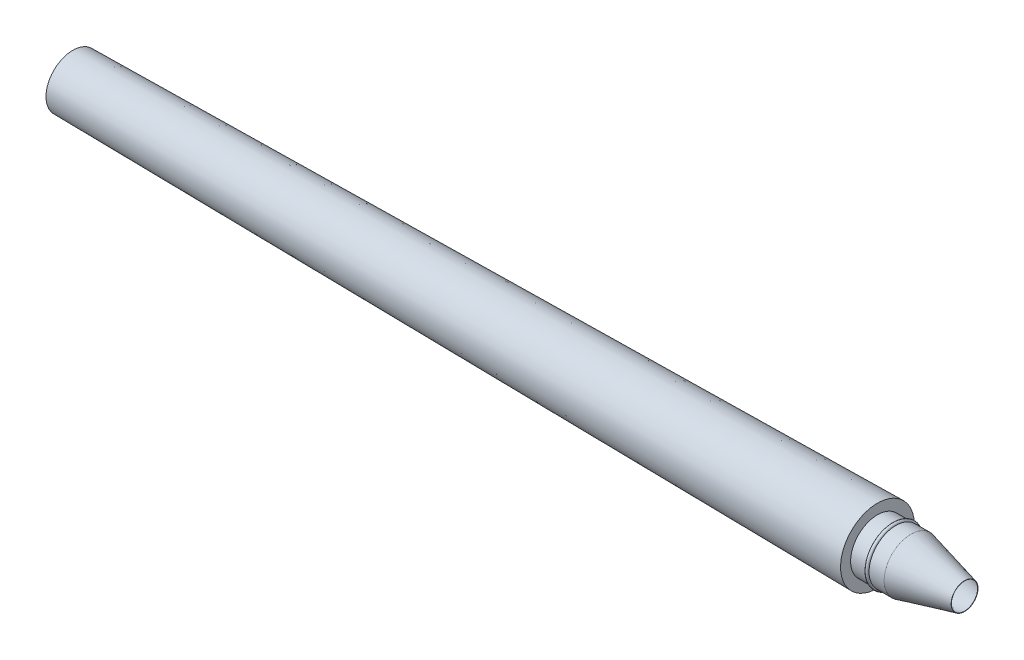
SolidWorks part; units mm, degrees
ref_plane "前视基准面" through (0, 0, 0) normal (0, 0, 1) x (1, 0, 0)
ref_plane "上视基准面" through (0, 0, 0) normal (0, 1, 0) x (1, 0, 0)
ref_plane "右视基准面" through (0, 0, 0) normal (1, 0, 0) x (0, 0, -1)
other "Configuration Table"
sketch "草图1" plane through (0, 0, 0) normal (0, 0, 1) x (1, 0, 0)
  line L0 (-66.5, 0) -> (-66.5, 4)
  line L1 (-66.5, 0) -> (66.5, 0) construction
  line L5 (66.5, 0) -> (53.5, 0) construction
  line L6 (53.5, 4) -> (55.75, 4)
  line L7 (-66.5, 4) -> (53.5, 5.5)
  line L8 (56.25, 4) -> (58.5, 4)
  line L9 (53.5, 5.5) -> (53.5, 4)
  line L10 (58.5, 4) -> (66.5, 2)
  arc A0 (56.25, 4) -> (55.75, 4) centre (56, 4) ccw
  point P0 (0, 0)
  point P4 (0, 0)
  dimension "D8" = 0.5
  dimension "D1" = 133
  dimension "D2" = 4
  dimension "D3" = 13
  dimension "D4" = 5.5
  dimension "D5" = 2
  dimension "D6" = 1.5
  dimension "D7" = 5
revolve "旋转-薄壁4" add sketch "草图1" angle 360 about L1
